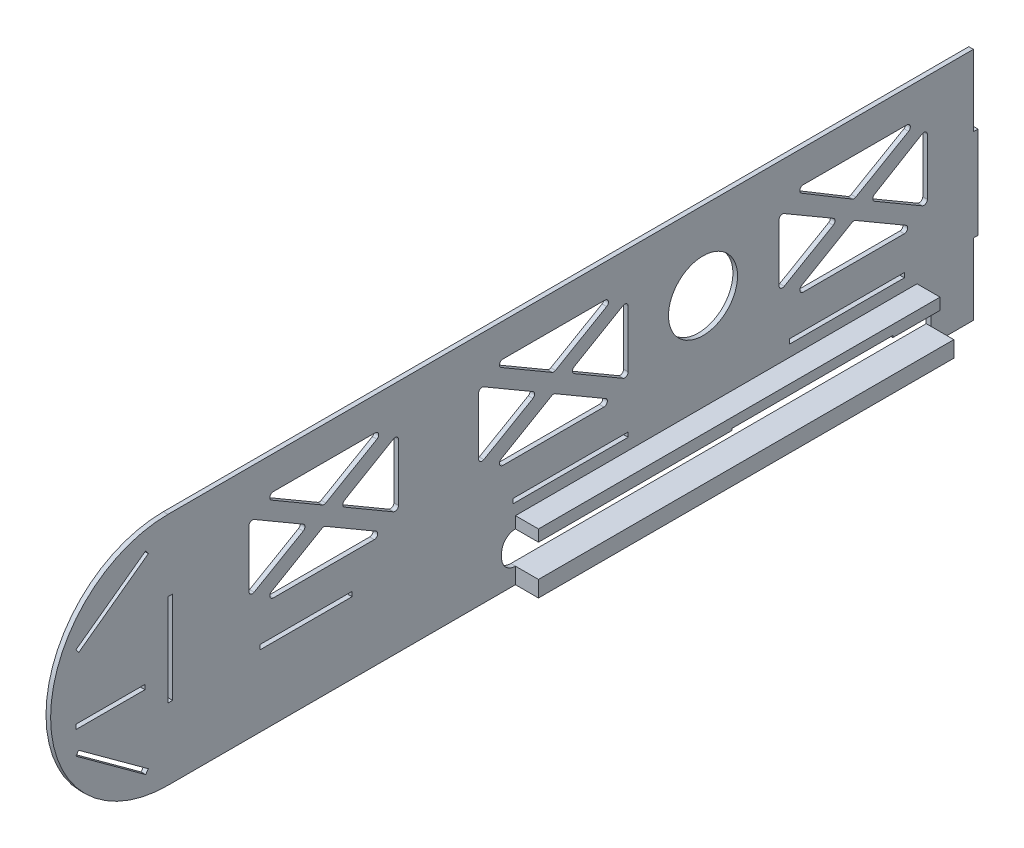
SolidWorks part; units mm, degrees
ref_plane "前视基准面" through (0, 0, 0) normal (0, 0, 1) x (1, 0, 0)
ref_plane "上视基准面" through (0, 0, 0) normal (0, 1, 0) x (1, 0, 0)
ref_plane "右视基准面" through (0, 0, 0) normal (1, 0, 0) x (0, 0, -1)
sketch "草图1" plane through (0, 0, 0) normal (1, 0, 0) x (0, 0, -1)
  line L0 (145, -36) -> (145, -38)
  line L1 (0, 51) -> (139, 51)
  line L2 (0, 51) -> (0, -51)
  line L3 (0, -51) -> (350, -51)
  line L4 (350, 51) -> (350, -51)
  line L5 (145, 51) -> (331.5, 51)
  line L6 (151, -44) -> (325.5, -44)
  line L7 (331.5, -36) -> (331.5, -39)
  line L8 (337.5, 51) -> (350, 51)
  line L10 (-40, -10) -> (-10, -10)
  line L11 (-40, -10) -> (-40, -8)
  line L12 (-40, -8) -> (-10, -8)
  line L13 (-10, -10) -> (-10, -8)
  line L49 (-40, 20) -> (-9.6982, 42.0918)
  line L50 (-40, 20) -> (-38.8218, 18.3839)
  line L51 (-9.6982, 42.0918) -> (-8.5199, 40.4757)
  line L52 (-38.8218, 18.3839) -> (-8.5199, 40.4757)
  line L53 (-51, 0) -> (0, 0)
  line L54 (-38.8218, -18.3839) -> (-8.5199, -40.4757)
  line L55 (-9.6982, -42.0918) -> (-8.5199, -40.4757)
  line L56 (-40, -20) -> (-38.8218, -18.3839)
  line L57 (-40, -20) -> (-9.6982, -42.0918)
  line L70 (350, 20) -> (352, 20)
  line L71 (350, 20) -> (350, -20)
  line L72 (352, 20) -> (352, -20)
  line L73 (350, -20) -> (352, -20)
  line L74 (0, 20) -> (0, -20)
  line L75 (0, 20) -> (2, 20)
  line L76 (0, -20) -> (2, -20)
  line L77 (2, 20) -> (2, -20)
  line L78 (139, 51) -> (145, 51)
  line L79 (331.5, 51) -> (337.5, 51)
  line L80 (151, -30) -> (325.5, -30)
  line L81 (151, -44) -> (151, -30)
  line L82 (331.5, -39) -> (331.5, -44)
  line L85 (325.5, -44) -> (331.5, -44)
  line L87 (235, -30) -> (305, -30)
  line L88 (235, -30) -> (235, -29.2)
  line L89 (235, -29.2) -> (305, -29.2)
  line L90 (305, -30) -> (305, -29.2)
  line L91 (145.5484, 36.6595) -> (189.8851, 36.6595)
  line L92 (135, 29.0479) -> (135, 4.2608)
  line L93 (145.5484, -3.3405) -> (189.4516, -3.3405)
  line L94 (200, 29.3884) -> (200, 4.6116)
  line L95 (176.5069, 15.7043) -> (197.7442, 3.3159)
  line L96 (158.585, 17.9016) -> (137.2558, 30.3436)
  line L97 (137.2514, 2.9626) -> (158.5806, 15.3077)
  line L98 (176.5069, 18.2957) -> (197.7442, 30.6841)
  line L99 (144.7926, 33.8638) -> (166.8743, 20.9828)
  line L100 (190.6365, 33.8613) -> (168.3815, 20.9803)
  line L101 (168.2558, 12.2603) -> (190.2074, -0.5448)
  line L102 (144.7926, -0.5448) -> (166.7442, 12.2603)
  line L103 (276.0709, 37) -> (321.089, 37)
  line L104 (265.5225, 28.9941) -> (265.5225, 4.207)
  line L105 (276.0709, -3.3943) -> (319.9742, -3.3943)
  line L106 (330, 28.9941) -> (330, 4.522)
  line L107 (307.0294, 15.31) -> (327.7442, 3.2264)
  line L108 (289.1076, 17.8477) -> (267.7784, 30.2898)
  line L109 (267.7739, 2.9088) -> (289.1032, 15.2538)
  line L110 (307.0153, 17.893) -> (327.7301, 30.2815)
  line L111 (275.2981, 34.2144) -> (297.3797, 20.9391)
  line L112 (321.8404, 34.2018) -> (298.904, 20.9265)
  line L113 (298.7784, 12.2065) -> (320.73, -0.5987)
  line L114 (275.3151, -0.5987) -> (297.2667, 12.2065)
  line L115 (40, -18) -> (80, -18)
  line L116 (40, -18) -> (40, -20)
  line L117 (80, -18) -> (80, -20)
  line L118 (40, -20) -> (80, -20)
  line L119 (150, -18) -> (200, -18)
  line L120 (150, -18) -> (150, -20)
  line L121 (200, -18) -> (200, -20)
  line L122 (150, -20) -> (200, -20)
  line L123 (270, -18) -> (320, -18)
  line L124 (270, -18) -> (270, -20)
  line L125 (320, -18) -> (320, -20)
  line L126 (270, -20) -> (320, -20)
  line L127 (45.7401, 36.6595) -> (90.0769, 36.6595)
  line L128 (35.1917, 29.0479) -> (35.1917, 4.2608)
  line L129 (45.7401, -3.3405) -> (89.6434, -3.3405)
  line L130 (100.1917, 29.0479) -> (100.1917, 4.271)
  line L131 (76.6986, 15.3638) -> (97.9359, 2.9754)
  line L132 (58.7768, 17.9016) -> (37.4476, 30.3436)
  line L133 (37.4431, 2.9626) -> (58.7724, 15.3077)
  line L134 (76.6986, 17.9552) -> (97.9359, 30.3436)
  line L135 (44.9843, 33.8638) -> (67.066, 20.9828)
  line L136 (90.8283, 33.8613) -> (68.5732, 20.9803)
  line L137 (68.4476, 12.2603) -> (90.3992, -0.5448)
  line L138 (44.9843, -0.5448) -> (66.9359, 12.2603)
  arc A0 (0, 51) -> (0, -51) centre (0, 0) ccw
  arc A3 (151, -44) -> (145, -38) centre (151, -38) cw
  arc A44 (331.5, -36) -> (325.5, -30) centre (325.5, -36) ccw
  arc A45 (151, -30) -> (145, -36) centre (151, -36) ccw
  arc A46 (97.9359, 30.3436) -> (100.1917, 29.0479) centre (98.6917, 29.0479) cw
  arc A47 (100.1917, 4.271) -> (97.9359, 2.9754) centre (98.6917, 4.271) cw
  arc A48 (197.7442, 30.6841) -> (200, 29.3884) centre (198.5, 29.3884) cw
  arc A49 (200, 4.6116) -> (197.7442, 3.3159) centre (198.5, 4.6116) cw
  arc A50 (176.5069, 15.7043) -> (176.5069, 18.2957) centre (177.2627, 17) cw
  arc A51 (158.585, 17.9016) -> (158.5806, 15.3077) centre (157.8292, 16.6059) cw
  arc A52 (137.2514, 2.9626) -> (135, 4.2608) centre (136.5, 4.2608) cw
  arc A53 (135, 29.0479) -> (137.2558, 30.3436) centre (136.5, 29.0479) cw
  arc A54 (144.7926, -0.5448) -> (145.5484, -3.3405) centre (145.5484, -1.8405) ccw
  arc A55 (189.4516, -3.3405) -> (190.2074, -0.5448) centre (189.4516, -1.8405) ccw
  arc A56 (168.2558, 12.2603) -> (166.7442, 12.2603) centre (167.5, 10.9646) ccw
  arc A57 (144.7926, 33.8638) -> (145.5484, 36.6595) centre (145.5484, 35.1595) cw
  arc A58 (189.8851, 36.6595) -> (190.6365, 33.8613) centre (189.8851, 35.1595) cw
  arc A59 (168.3815, 20.9803) -> (166.8743, 20.9828) centre (167.6301, 22.2785) cw
  arc A60 (327.7301, 30.2815) -> (330, 28.9941) centre (328.5, 28.9941) cw
  arc A61 (330, 4.522) -> (327.7442, 3.2264) centre (328.5, 4.522) cw
  arc A62 (307.0294, 15.31) -> (307.0153, 17.893) centre (307.7852, 16.6057) cw
  arc A63 (289.1076, 17.8477) -> (289.1032, 15.2538) centre (288.3518, 16.5521) cw
  arc A64 (267.7739, 2.9088) -> (265.5225, 4.207) centre (267.0225, 4.207) cw
  arc A65 (265.5225, 28.9941) -> (267.7784, 30.2898) centre (267.0225, 28.9941) cw
  arc A66 (275.3151, -0.5987) -> (276.0709, -3.3943) centre (276.0709, -1.8943) ccw
  arc A67 (319.9742, -3.3943) -> (320.73, -0.5987) centre (319.9742, -1.8943) ccw
  arc A68 (298.7784, 12.2065) -> (297.2667, 12.2065) centre (298.0225, 10.9108) ccw
  arc A69 (275.2981, 34.2144) -> (276.0709, 37) centre (276.0709, 35.5) cw
  arc A70 (321.089, 37) -> (321.8404, 34.2018) centre (321.089, 35.5) cw
  arc A71 (298.904, 20.9265) -> (297.3797, 20.9391) centre (298.1526, 22.2247) cw
  circle A72 centre (232.5, 17) radius 15
  arc A73 (76.6986, 15.3638) -> (76.6986, 17.9552) centre (77.4544, 16.6595) cw
  arc A74 (58.7768, 17.9016) -> (58.7724, 15.3077) centre (58.021, 16.6059) cw
  arc A75 (37.4431, 2.9626) -> (35.1917, 4.2608) centre (36.6917, 4.2608) cw
  arc A76 (35.1917, 29.0479) -> (37.4476, 30.3436) centre (36.6917, 29.0479) cw
  arc A77 (44.9843, -0.5448) -> (45.7401, -3.3405) centre (45.7401, -1.8405) ccw
  arc A78 (89.6434, -3.3405) -> (90.3992, -0.5448) centre (89.6434, -1.8405) ccw
  arc A79 (68.4476, 12.2603) -> (66.9359, 12.2603) centre (67.6917, 10.9646) ccw
  arc A80 (44.9843, 33.8638) -> (45.7401, 36.6595) centre (45.7401, 35.1595) cw
  arc A81 (90.0769, 36.6595) -> (90.8283, 33.8613) centre (90.0769, 35.1595) cw
  arc A82 (68.5732, 20.9803) -> (67.066, 20.9828) centre (67.8218, 22.2785) cw
  point P5 (40.1917, 36.6595)
  point P7 (331.5, -44)
  point P8 (286.5, 50)
  point P21 (145, -44)
  point P24 (95.6629, 36.6595)
  point P28 (40.1917, -3.3405)
  point P29 (95.1917, -3.3405)
  point P30 (40.1917, -3.3405)
  point P31 (35.1917, 1.6595)
  point P32 (100, -45)
  point P33 (100.1917, 1.6595)
  point P34 (100.1917, 31.6595)
  point P35 (35.1917, 31.6595)
  point P53 (140, 36.6595)
  point P58 (195.4712, 36.6595)
  point P59 (140, -3.3405)
  point P60 (195, -3.3405)
  point P61 (140, -3.3405)
  point P62 (135, 1.6595)
  point P63 (200, 2)
  point P64 (200, 32)
  point P65 (135, 31.6595)
  point P113 (270.5225, 37)
  point P118 (325.9937, 37)
  point P119 (270.5225, -3.3943)
  point P120 (325.5225, -3.3943)
  point P121 (270.5225, -3.3943)
  point P122 (265.5225, 1.6057)
  point P123 (330, 1.6057)
  point P124 (330, 31.6057)
  point P125 (265.5225, 31.6057)
  point P169 (350, -20)
  point P182 (-9.6982, -42.0918)
  point P184 (-40, -20)
  point P189 (352, 20)
  point P190 (352, -20)
  point P198 (350, 20)
  dimension "D1" = 1.5
  dimension "D2" = 1.5
  dimension "D3" = 1.5
  dimension "D5" = 1.5
  dimension "D6" = 1.5
  dimension "D7" = 1.5
  dimension "D8" = 1.5
  dimension "D9" = 1.5
  dimension "D10" = 1.5
  dimension "D11" = 1.5
  dimension "D12" = 1.5
  dimension "D13" = 1.5
  dimension "D14" = 1.5
  dimension "D15" = 1.5
  dimension "D16" = 1.5
  dimension "D17" = 1.5
  dimension "D18" = 1.5
  dimension "D19" = 1.5
  dimension "D20" = 1.5
  dimension "D21" = 1.5
  dimension "D22" = 1.5
  dimension "D23" = 1.5
  dimension "D24" = 1.5
  dimension "D25" = 1.5
  dimension "D26" = 1.5
  dimension "D27" = 1.5
  dimension "D28" = 1.5
  dimension "D29" = 1.5
  dimension "D30" = 1.5
  dimension "D31" = 1.5
  dimension "D32" = 1.5
  dimension "D33" = 1.5
  dimension "D34" = 1.5
  dimension "D35" = 1.5
  dimension "D36" = 1.5
  dimension "D37" = 1.5
  dimension "D41" = 2
  dimension "D42" = 37.5
  dimension "D43" = 2
extrude "凸台-拉伸3" add sketch "草图1" along normal blind 2
sketch "草图2" plane through (2, 0, 0) normal (1, 0, 0) x (0, 0, -1)
  line L0 (151, -44) -> (151, -51)
  line L1 (0, -51) -> (350, -51) construction
  line L2 (151, -44) -> (331.5, -44)
  line L3 (331.5, -44) -> (331.5, -51)
  line L4 (331.5, -51) -> (151, -51)
  line L5 (151, -30) -> (235, -30)
  line L6 (235, -30) -> (235, -29.2)
  line L7 (235, -29.2) -> (305, -29.2)
  line L8 (305, -29.2) -> (305, -30)
  line L9 (305, -30) -> (325.5, -30)
  line L10 (325.5, -30) -> (325.5, -25)
  line L11 (325.5, -25) -> (151, -25)
  line L12 (151, -25) -> (151, -30)
  arc A0 (151, -30) -> (145, -36) centre (151, -36) ccw construction
extrude "凸台-拉伸4" add sketch "草图2" along normal blind 10
